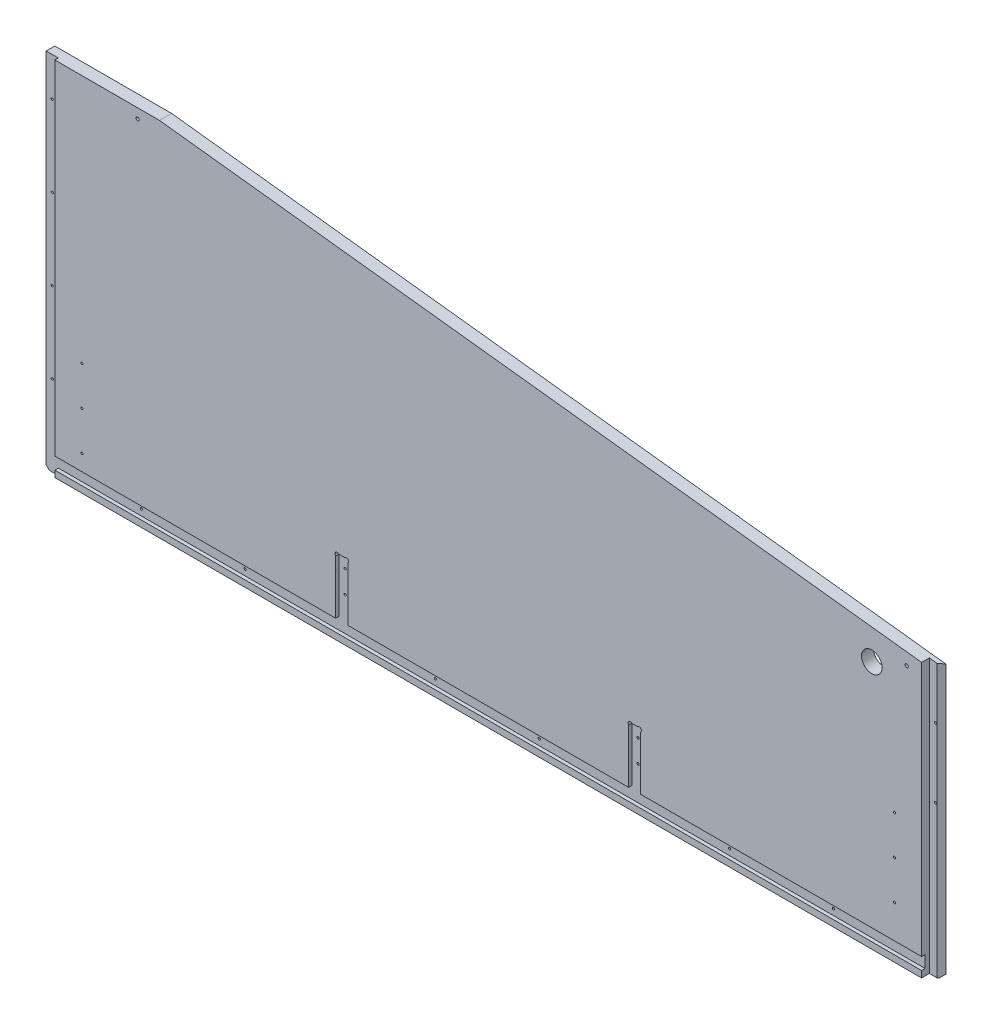
SolidWorks part; units mm, degrees
material "Pine"
ref_plane "Front Plane" through (0, 0, 0) normal (0, 0, 1) x (1, 0, 0)
ref_plane "Top Plane" through (0, 0, 0) normal (0, 1, 0) x (1, 0, 0)
ref_plane "Right Plane" through (0, 0, 0) normal (1, 0, 0) x (0, 0, -1)
sketch "Sketch1" plane through (0, 0, 0) normal (0, 0, 1) x (1, 0, 0)
  line L0 (8932.6508, -5243.5125) -> (10226.1458, -5243.5125)
  line L1 (9086.3208, -4722.0918) -> (10222.9708, -4853.7812)
  line L2 (8914.8708, -6342.0625) -> (10197.5708, -6342.0625)
  line L3 (8914.8708, -5808.6625) -> (10197.5708, -5808.6625)
  line L4 (8919.6333, -5253.0375) -> (10218.2083, -5253.0375)
  line L5 (9134.2633, -4656.1375) -> (9134.2633, -4638.3575)
  line L6 (9091.0833, -4638.3575) -> (9134.2633, -4638.3575)
  line L7 (9091.0833, -4567.2375) -> (9091.0833, -4638.3575)
  line L8 (9134.2633, -4656.1375) -> (9581.3033, -4656.1375)
  line L9 (9091.0833, -4567.2375) -> (9624.4833, -4567.2375)
  line L10 (9581.3033, -4656.1375) -> (9581.3033, -4638.3575)
  line L11 (9581.3033, -4638.3575) -> (9624.4833, -4638.3575)
  line L12 (9624.4833, -4567.2375) -> (9624.4833, -4638.3575)
  line L13 (8932.6508, -5225.7325) -> (9344.9775, -5225.7325)
  line L14 (8932.6508, -5256.2125) -> (8932.6508, -5243.5125)
  line L15 (8911.6958, -5256.2125) -> (8932.6508, -5256.2125)
  line L16 (8914.8708, -4722.0918) -> (9086.3208, -4722.0918)
  line L17 (8911.6958, -4715.5913) -> (8932.6508, -4715.5913)
  line L18 (8914.8708, -6342.0625) -> (8914.8708, -5808.6625)
  line L19 (12082.9917, -4722.0918) -> (10946.3417, -4853.7812)
  line L20 (12236.6617, -5243.5125) -> (10943.1667, -5243.5125)
  line L21 (10951.1042, -5253.0375) -> (12249.6792, -5253.0375)
  line L22 (10838.3917, -5656.2625) -> (11308.2917, -5656.2625)
  line L23 (10838.3917, -5719.7625) -> (11308.2917, -5719.7625)
  line L24 (10838.3917, -5742.5368) -> (11308.2917, -5742.5368)
  line L25 (10806.6417, -6342.0625) -> (11340.0417, -6342.0625)
  line L26 (10803.4667, -6335.7125) -> (11343.2167, -6335.7125)
  line L27 (10803.4667, -6317.9325) -> (11343.2167, -6317.9325)
  line L28 (10943.1667, -5225.7325) -> (11376.4483, -5225.7325)
  line L29 (11506.7292, -4754.5625) -> (10806.6417, -4827.5875)
  line L30 (11506.7292, -4567.2375) -> (11506.7292, -4754.5625)
  line L31 (10806.6417, -4567.2375) -> (10806.6417, -4827.5875)
  line L32 (10806.6417, -4567.2375) -> (11506.7292, -4567.2375)
  line L33 (10235.6708, -6329.3625) -> (10245.1958, -6329.3625)
  line L34 (10245.1958, -6329.3625) -> (10254.7208, -6278.5625)
  line L35 (10302.3458, -6329.3625) -> (10311.8708, -6278.5625)
  line L36 (10302.3458, -6329.3625) -> (10292.8208, -6329.3625)
  line L37 (10245.1958, -5821.3625) -> (10254.7208, -5872.1625)
  line L38 (10235.6708, -5821.3625) -> (10245.1958, -5821.3625)
  line L39 (10292.8208, -5821.3625) -> (10302.3458, -5821.3625)
  line L40 (10302.3458, -5821.3625) -> (10311.8708, -5872.1625)
  line L41 (10235.6708, -5821.3625) -> (10235.6708, -6329.3625)
  line L42 (10254.7208, -5872.1625) -> (10254.7208, -6278.5625)
  line L43 (10311.8708, -5872.1625) -> (10311.8708, -6278.5625)
  line L44 (10292.8208, -5821.3625) -> (10292.8208, -6329.3625)
  line L45 (8932.6508, -5225.7325) -> (8932.6508, -4715.5913)
  line L46 (8911.6958, -4715.5913) -> (8911.6958, -5256.2125)
  line L47 (8914.8708, -5248.275) -> (8914.8708, -4722.0918)
  line L48 (8919.6333, -5253.0375) -> (8914.8708, -5248.275)
  line L49 (8914.8708, -5145.0875) -> (8937.426, -5145.0875)
  line L50 (8914.8708, -5202.2375) -> (8937.426, -5202.2375)
  line L51 (10838.3917, -5656.2625) -> (10838.3917, -5719.7625)
  line L52 (10832.0417, -5736.1868) -> (10856.1717, -5736.1868)
  line L53 (10806.6417, -6342.0625) -> (10806.6417, -5818.7368)
  line L54 (10832.0417, -5649.9125) -> (10856.1717, -5649.9125)
  line L55 (10832.0417, -5726.1125) -> (10856.1717, -5726.1125)
  line L56 (10806.6417, -5818.7368) -> (10833.9015, -5818.7368)
  line L57 (10832.0417, -5806.0442) -> (10851.6815, -5806.0442)
  line L58 (10856.1717, -5801.5541) -> (10856.1717, -5736.1868)
  line L59 (10838.3917, -5814.2467) -> (10838.3917, -5742.5368)
  line L60 (10832.0417, -5806.0442) -> (10832.0417, -5736.1868)
  line L61 (10803.4667, -6317.9325) -> (10803.4667, -6335.7125)
  line L62 (10197.5708, -5808.6625) -> (10197.5708, -6342.0625)
  line L63 (9762.3842, -6348.4125) -> (9762.3842, -5802.3125)
  line L64 (9780.1642, -6348.4125) -> (9762.3842, -6348.4125)
  line L65 (9780.1642, -5802.3125) -> (9780.1642, -6348.4125)
  line L66 (9762.3842, -5802.3125) -> (9780.1642, -5802.3125)
  line L67 (9332.2775, -6348.4125) -> (9332.2775, -5802.3125)
  line L68 (9332.2775, -6348.4125) -> (9350.0575, -6348.4125)
  line L69 (9350.0575, -5802.3125) -> (9350.0575, -6348.4125)
  line L70 (9332.2775, -5802.3125) -> (9350.0575, -5802.3125)
  line L71 (9993.8374, -6061.075) -> (9993.8374, -6045.2418)
  line L72 (9998.5999, -6065.8375) -> (10014.4331, -6065.8375)
  line L73 (9998.5999, -6084.8875) -> (10014.4331, -6084.8875)
  line L74 (9993.8374, -6105.4832) -> (9993.8374, -6089.65)
  line L75 (9974.7874, -6105.4832) -> (9974.7874, -6089.65)
  line L76 (9954.1917, -6084.8875) -> (9970.0249, -6084.8875)
  line L77 (9974.7874, -6061.075) -> (9974.7874, -6045.2418)
  line L78 (9954.1917, -6065.8375) -> (9970.0249, -6065.8375)
  line L79 (10793.9417, -6237.2875) -> (10816.4969, -6237.2875)
  line L80 (10793.9417, -6294.4375) -> (10816.4969, -6294.4375)
  line L81 (10856.1717, -5649.9125) -> (10856.1717, -5726.1125)
  line L82 (10832.0417, -5726.1125) -> (10832.0417, -5649.9125)
  line L83 (10226.1458, -5225.7325) -> (10226.1458, -5243.5125)
  line L84 (10205.1908, -5257.8) -> (10205.1908, -4844.2499)
  line L85 (10230.9083, -4844.2499) -> (10230.9083, -5257.8)
  line L86 (10205.1908, -5257.8) -> (10230.9083, -5257.8)
  line L87 (10205.1908, -4844.2499) -> (10230.9083, -4844.2499)
  line L88 (10946.3417, -5176.8375) -> (10968.8969, -5176.8375)
  line L89 (9349.4676, -5141.9125) -> (9358.2674, -5141.9125)
  line L90 (10946.3417, -5119.6875) -> (10968.8969, -5119.6875)
  line L91 (9929.011, -4660.9635) -> (10066.0807, -4660.9635)
  line L92 (9929.011, -4678.7435) -> (10066.0807, -4678.7435)
  line L93 (10943.1667, -5225.7325) -> (10943.1667, -5243.5125)
  line L94 (10946.3417, -5248.275) -> (10951.1042, -5253.0375)
  line L95 (10946.3417, -5257.8063) -> (10946.3417, -4849.0188)
  line L96 (10964.1217, -5257.8) -> (10964.1217, -4844.2499)
  line L97 (10938.4042, -4844.2499) -> (10938.4042, -5257.8)
  line L98 (10938.4042, -5257.8) -> (10964.1217, -5257.8)
  line L99 (10964.1217, -4844.2499) -> (10938.4042, -4844.2499)
  line L100 (10344.8908, -4560.8875) -> (10369.0208, -4560.8875)
  line L101 (10344.8908, -4560.8875) -> (10369.0208, -4560.8875)
  line L102 (10800.2917, -4560.8875) -> (10824.4217, -4560.8875)
  line L103 (10200.4156, -5119.6875) -> (10222.9708, -5119.6875)
  line L104 (10200.4156, -5176.8375) -> (10222.9708, -5176.8375)
  line L105 (9344.9775, -5146.4026) -> (9344.9775, -5225.7325)
  line L106 (10344.8908, -4560.8875) -> (10344.8908, -4833.9375)
  line L107 (9792.8642, -5225.7325) -> (9792.8642, -5146.4026)
  line L108 (9362.7575, -5225.7325) -> (9775.0842, -5225.7325)
  line L109 (9680.3633, -4761.8396) -> (9680.3633, -4559.9604)
  line L110 (9656.2333, -4559.9604) -> (9680.3633, -4559.9604)
  line L111 (9656.2333, -4761.8396) -> (9680.3633, -4761.8396)
  line L112 (9656.2333, -4761.8396) -> (9656.2333, -4559.9604)
  line L113 (9779.5743, -5141.9125) -> (9788.374, -5141.9125)
  line L114 (10070.5708, -4665.4536) -> (10070.5708, -4674.2534)
  line L115 (9924.5208, -4674.2534) -> (9924.5208, -4665.4536)
  line L116 (12127.4417, -6188.3925) -> (12205.5015, -6188.3925)
  line L117 (12209.9917, -6170.6125) -> (12209.9917, -6183.9024)
  line L118 (9792.8642, -5225.7325) -> (10226.1458, -5225.7325)
  line L119 (9662.5833, -4754.5625) -> (10362.6708, -4827.5875)
  line L120 (9662.5833, -4567.2375) -> (9662.5833, -4754.5625)
  line L121 (10362.6708, -4567.2375) -> (10362.6708, -4827.5875)
  line L122 (9662.5833, -4567.2375) -> (10362.6708, -4567.2375)
  line L123 (10824.4217, -4833.9375) -> (10800.2917, -4833.9375)
  line L124 (10800.2917, -4833.9375) -> (10800.2917, -4560.8875)
  line L125 (10824.4217, -4560.8875) -> (10824.4217, -4833.9375)
  line L126 (10344.8908, -4833.9375) -> (10369.0208, -4833.9375)
  line L127 (10369.0208, -4833.9375) -> (10369.0208, -4560.8875)
  line L128 (10222.9708, -5248.275) -> (10218.2083, -5253.0375)
  line L129 (10222.9708, -5257.8063) -> (10222.9708, -4849.0188)
  line L130 (11734.6544, -5701.375) -> (11739.2301, -5701.375)
  line L131 (9362.7575, -5225.7325) -> (9362.7575, -5146.4026)
  line L132 (9775.0842, -5146.4026) -> (9775.0842, -5225.7325)
  line L133 (11761.3864, -5701.375) -> (11756.8282, -5701.375)
  line L134 (11734.6544, -5693.755) -> (11739.2301, -5693.755)
  line L135 (11761.4039, -5693.755) -> (11756.8282, -5693.755)
  line L136 (11734.6544, -5701.375) -> (11739.2301, -5701.375)
  line L137 (11744.3462, -5721.3024) -> (11744.3462, -5706.4179)
  line L138 (11751.7122, -5721.3024) -> (11751.7122, -5706.4179)
  line L139 (11740.0917, -6170.6125) -> (11740.0917, -6183.9024)
  line L140 (11689.2917, -6188.3925) -> (11822.6417, -6188.3925)
  line L141 (11689.2917, -6348.4093) -> (11689.2917, -6164.2657)
  line L142 (11689.2917, -6164.2657) -> (11746.4417, -6164.2657)
  line L143 (11746.4417, -6164.2657) -> (11746.4417, -6188.3925)
  line L144 (11689.2917, -6164.2657) -> (11746.4417, -6164.2657)
  line L145 (11340.0417, -5818.7368) -> (11340.0417, -6342.0625)
  line L146 (11290.5117, -5726.1125) -> (11314.6417, -5726.1125)
  line L147 (11290.5117, -5649.9125) -> (11290.5117, -5726.1125)
  line L148 (11340.0417, -5818.7368) -> (11312.7818, -5818.7368)
  line L149 (11314.6417, -5806.0442) -> (11295.0018, -5806.0442)
  line L150 (11290.5117, -5801.5541) -> (11290.5117, -5736.1868)
  line L151 (11308.2917, -5814.2467) -> (11308.2917, -5742.5368)
  line L152 (11314.6417, -5806.0442) -> (11314.6417, -5736.1868)
  line L153 (11290.5117, -5736.1868) -> (11314.6417, -5736.1868)
  line L154 (11848.0417, -6267.1325) -> (11962.3417, -6267.1325)
  line L155 (11962.3417, -6267.1325) -> (11962.3417, -6203.6325)
  line L156 (11343.2167, -6317.9325) -> (11343.2167, -6335.7125)
  line L157 (11365.4417, -5656.2625) -> (11365.4417, -5719.7625)
  line L158 (11365.4417, -5656.2625) -> (11479.7417, -5656.2625)
  line L159 (11778.1917, -6071.3937) -> (11802.3217, -6071.3937)
  line L160 (11314.6417, -5726.1125) -> (11314.6417, -5649.9125)
  line L161 (11314.6417, -5649.9125) -> (11290.5117, -5649.9125)
  line L162 (11308.2917, -5719.7625) -> (11308.2917, -5656.2625)
  line L163 (11689.2917, -6348.4093) -> (11713.4217, -6348.4093)
  line L164 (12203.6417, -6164.2657) -> (12260.7917, -6164.2657)
  line L165 (11713.4217, -6348.4093) -> (11713.4217, -6164.2657)
  line L166 (11695.6417, -6342.0625) -> (11695.6417, -6170.6125)
  line L167 (11695.6417, -6048.5337) -> (11699.4517, -6052.3437)
  line L168 (11822.6417, -6292.5325) -> (11822.6417, -6188.3925)
  line L169 (11695.6417, -6342.0625) -> (11695.6417, -6170.6125)
  line L170 (11848.0417, -6203.6325) -> (11962.3417, -6203.6325)
  line L171 (11848.0417, -6203.6325) -> (11848.0417, -6267.1325)
  line L172 (11987.7417, -6267.1325) -> (11987.7417, -6203.6325)
  line L173 (11784.5417, -6077.7437) -> (11784.5417, -6141.2438)
  line L174 (11517.8417, -5656.2625) -> (11632.1417, -5656.2625)
  line L175 (11632.1417, -5656.2625) -> (11632.1417, -5719.7625)
  line L176 (11632.1417, -5719.7625) -> (11517.8417, -5719.7625)
  line L177 (11517.8417, -5719.7625) -> (11517.8417, -5656.2625)
  line L178 (11692.4667, -6028.2137) -> (11692.4667, -6045.9937)
  line L179 (11695.6417, -5979.3188) -> (11718.1969, -5979.3188)
  line L180 (11695.6417, -5922.1687) -> (11718.1969, -5922.1687)
  line L181 (11821.0415, -5722.9375) -> (11821.0415, -5943.6)
  line L182 (11687.7042, -5651.5) -> (11701.9917, -5651.5)
  line L183 (11687.7042, -5651.5) -> (11687.7042, -6055.5251)
  line L184 (11687.7042, -6055.5251) -> (11701.9917, -6055.5251)
  line L185 (11701.9917, -6055.5251) -> (11701.9917, -5651.5)
  line L186 (11695.6417, -6055.2013) -> (11695.6417, -5649.595)
  line L187 (11695.6417, -5656.2625) -> (11695.6417, -6048.5337)
  line L188 (11695.6417, -6170.6125) -> (11740.0917, -6170.6125)
  line L189 (12203.6417, -6164.2657) -> (12203.6417, -6188.3925)
  line L190 (12254.4417, -6342.0625) -> (12254.4417, -6170.6125)
  line L191 (12129.0419, -5943.6) -> (12129.0419, -5722.9375)
  line L192 (12254.4417, -6048.5337) -> (12250.6317, -6052.3437)
  line L193 (12257.6167, -6045.9937) -> (12257.6167, -6028.2137)
  line L194 (12248.0917, -5651.5) -> (12262.3792, -5651.5)
  line L195 (12262.3792, -5651.5) -> (12262.3792, -6055.5251)
  line L196 (12262.3792, -6055.5251) -> (12248.0917, -6055.5251)
  line L197 (12248.0917, -6055.5251) -> (12248.0917, -5651.5)
  line L198 (12254.4417, -6141.2438) -> (12254.4417, -6077.7437)
  line L199 (12236.6617, -6164.2657) -> (12260.7917, -6164.2657)
  line L200 (12102.0417, -6267.1325) -> (11987.7417, -6267.1325)
  line L201 (11330.1865, -6237.2875) -> (11352.7417, -6237.2875)
  line L202 (11330.1865, -6294.4375) -> (11352.7417, -6294.4375)
  line L203 (11474.6617, -5851.8425) -> (11492.4417, -5851.8425)
  line L204 (11474.6617, -5808.6625) -> (11474.6617, -5851.8425)
  line L205 (11403.5417, -5808.6625) -> (11474.6617, -5808.6625)
  line L206 (11492.4417, -5851.8425) -> (11492.4417, -6298.8825)
  line L207 (11403.5417, -6342.0625) -> (11403.5417, -5808.6625)
  line L208 (11474.6617, -6298.8825) -> (11492.4417, -6298.8825)
  line L209 (11474.6617, -6342.0625) -> (11474.6617, -6298.8825)
  line L210 (11403.5417, -6342.0625) -> (11474.6617, -6342.0625)
  line L211 (11619.4417, -5851.8425) -> (11601.6617, -5851.8425)
  line L212 (11601.6617, -5808.6625) -> (11601.6617, -5851.8425)
  line L213 (11530.5417, -5808.6625) -> (11601.6617, -5808.6625)
  line L214 (11619.4417, -5851.8425) -> (11619.4417, -6298.8825)
  line L215 (11530.5417, -6342.0625) -> (11530.5417, -5808.6625)
  line L216 (11619.4417, -6298.8825) -> (11601.6617, -6298.8825)
  line L217 (11601.6617, -6342.0625) -> (11601.6617, -6298.8825)
  line L218 (11530.5417, -6342.0625) -> (11601.6617, -6342.0625)
  line L219 (11479.7417, -5719.7625) -> (11479.7417, -5656.2625)
  line L220 (11365.4417, -5719.7625) -> (11479.7417, -5719.7625)
  line L221 (11778.1917, -6147.5937) -> (11802.3217, -6147.5937)
  line L222 (11802.3217, -6071.3937) -> (11802.3217, -6147.5937)
  line L223 (11778.1917, -6147.5937) -> (11778.1917, -6071.3937)
  line L224 (12254.4417, -5922.1687) -> (12231.8865, -5922.1687)
  line L225 (12254.4417, -5979.3188) -> (12231.8865, -5979.3188)
  line L226 (12254.4417, -6055.2013) -> (12254.4417, -5649.595)
  line L227 (12254.4417, -6048.5337) -> (12254.4417, -5656.2625)
  line L228 (11841.6917, -5702.2873) -> (12108.3917, -5702.2873)
  line L229 (11822.6417, -6292.5325) -> (12127.4417, -6292.5325)
  line L230 (12127.4417, -6292.5325) -> (12127.4417, -6188.3925)
  line L231 (12254.4417, -6170.6125) -> (12209.9917, -6170.6125)
  line L232 (11695.6417, -6342.0625) -> (12254.4417, -6342.0625)
  line L233 (12236.6617, -6348.4093) -> (12260.7917, -6348.4093)
  line L234 (12260.7917, -6348.4093) -> (12260.7917, -6164.2657)
  line L235 (12236.6617, -6348.4093) -> (12236.6617, -6164.2657)
  line L236 (12102.0417, -6203.6325) -> (12102.0417, -6267.1325)
  line L237 (11987.7417, -6203.6325) -> (12102.0417, -6203.6325)
  line L238 (12236.6617, -6147.5937) -> (12236.6617, -6071.3937)
  line L239 (12203.6417, -6188.3925) -> (12260.7917, -6188.3925)
  line L240 (11098.7417, -4665.4536) -> (11098.7417, -4674.2534)
  line L241 (11394.2283, -5146.4026) -> (11394.2283, -5225.7325)
  line L242 (11376.4483, -5225.7325) -> (11376.4483, -5146.4026)
  line L243 (11394.2283, -5225.7325) -> (11806.555, -5225.7325)
  line L244 (11841.6917, -5964.2502) -> (12108.3917, -5964.2502)
  line L245 (12236.6617, -6147.5937) -> (12260.7917, -6147.5937)
  line L246 (12236.6617, -5256.2125) -> (12236.6617, -5243.5125)
  line L247 (12260.7917, -6147.5937) -> (12260.7917, -6071.3937)
  line L248 (12260.7917, -6071.3937) -> (12236.6617, -6071.3937)
  line L249 (12254.4417, -6077.7437) -> (11784.5417, -6077.7437)
  line L250 (11784.5417, -6141.2438) -> (12254.4417, -6141.2438)
  line L252 (12254.4417, -5656.2625) -> (11695.6417, -5656.2625)
  line L253 (11699.4517, -6052.3437) -> (12250.6317, -6052.3437)
  line L254 (11692.4667, -6045.9937) -> (12257.6167, -6045.9937)
  line L255 (11692.4667, -6028.2137) -> (12257.6167, -6028.2137)
  line L256 (11824.335, -5146.4026) -> (11824.335, -5225.7325)
  line L257 (11811.0451, -5141.9125) -> (11819.8449, -5141.9125)
  line L258 (11244.7917, -4674.2534) -> (11244.7917, -4665.4536)
  line L259 (11806.555, -5225.7325) -> (11806.555, -5146.4026)
  line L260 (11488.9492, -4761.8396) -> (11488.9492, -4559.9604)
  line L261 (11488.9492, -4559.9604) -> (11513.0792, -4559.9604)
  line L262 (11488.9492, -4761.8396) -> (11513.0792, -4761.8396)
  line L263 (11513.0792, -4761.8396) -> (11513.0792, -4559.9604)
  line L264 (11240.3015, -4660.9635) -> (11103.2318, -4660.9635)
  line L265 (11103.2318, -4678.7435) -> (11240.3015, -4678.7435)
  line L266 (12236.6617, -5225.7325) -> (12236.6617, -4715.5913)
  line L267 (12257.6167, -4715.5913) -> (12257.6167, -5256.2125)
  line L268 (12254.4417, -5248.275) -> (12254.4417, -4722.0918)
  line L269 (12236.6617, -5225.7325) -> (11824.335, -5225.7325)
  line L270 (12035.0492, -4656.1375) -> (12035.0492, -4638.3575)
  line L271 (12078.2292, -4638.3575) -> (12035.0492, -4638.3575)
  line L272 (12078.2292, -4567.2375) -> (12078.2292, -4638.3575)
  line L273 (12035.0492, -4656.1375) -> (11588.0092, -4656.1375)
  line L274 (11544.8292, -4567.2375) -> (12078.2292, -4567.2375)
  line L275 (11588.0092, -4656.1375) -> (11588.0092, -4638.3575)
  line L276 (11544.8292, -4638.3575) -> (11588.0092, -4638.3575)
  line L277 (11544.8292, -4567.2375) -> (11544.8292, -4638.3575)
  line L278 (12249.6792, -5253.0375) -> (12254.4417, -5248.275)
  line L280 (12257.6167, -5256.2125) -> (12236.6617, -5256.2125)
  line L281 (12231.8865, -5145.0875) -> (12254.4417, -5145.0875)
  line L282 (12231.8865, -5202.2375) -> (12254.4417, -5202.2375)
  line L283 (12236.6617, -4715.5913) -> (12257.6167, -4715.5913)
  line L284 (12082.9917, -4722.0918) -> (12254.4417, -4722.0918)
  line L285 (11380.9385, -5141.9125) -> (11389.7382, -5141.9125)
  circle A0 centre (8923.7608, -4778.9042) radius 1.5875
  circle A1 centre (9062.6598, -4736.3765) radius 2.3685
  circle A2 centre (9051.3958, -6281.7375) radius 22.225
  circle A3 centre (9083.1458, -6249.9875) radius 1.5875
  circle A4 centre (9083.1458, -6313.4875) radius 1.5875
  circle A5 centre (9019.6458, -6249.9875) radius 1.5875
  circle A6 centre (9019.6458, -6313.4875) radius 1.5875
  circle A7 centre (8972.3383, -5202.2375) radius 1.5875
  circle A8 centre (8923.7608, -5015.9708) radius 1.5875
  circle A9 centre (8923.7608, -5134.5042) radius 1.5875
  circle A10 centre (9054.5708, -5234.6225) radius 1.5875
  circle A11 centre (8923.7608, -4897.4375) radius 1.5875
  circle A12 centre (8972.3383, -5087.9375) radius 1.5875
  circle A13 centre (8972.3383, -5145.0875) radius 1.5875
  circle A14 centre (10847.2817, -5668.9625) radius 1.5875
  circle A15 centre (10847.2817, -5707.0625) radius 1.5875
  circle A16 centre (10847.2817, -5755.2368) radius 1.5875
  circle A17 centre (10851.4092, -6237.2875) radius 1.5875
  circle A18 centre (10851.4092, -6294.4375) radius 1.5875
  circle A19 centre (10847.2817, -5793.3442) radius 1.5875
  arc A20 (10833.9015, -5818.7368) -> (10838.3917, -5814.2467) centre (10836.1466, -5816.4918) ccw
  arc A21 (10851.6815, -5806.0442) -> (10856.1717, -5801.5541) centre (10853.9266, -5803.7992) ccw
  circle A22 centre (10882.8417, -6040.4375) radius 1.5875
  circle A23 centre (10882.8417, -6218.2375) radius 1.5875
  circle A24 centre (10882.8417, -5862.6375) radius 1.5875
  circle A25 centre (10908.2417, -6326.8225) radius 1.5875
  circle A26 centre (10908.2417, -6326.8225) radius 1.5875
  circle A27 centre (10851.4092, -6180.1375) radius 1.5875
  circle A28 centre (10815.5317, -4783.4231) radius 1.5875
  circle A29 centre (10815.5317, -4696.9488) radius 1.5875
  circle A30 centre (10815.5317, -4610.4746) radius 1.5875
  circle A31 centre (10979.1323, -4867.0082) radius 2.3685
  circle A32 centre (10190.1802, -4867.0082) radius 2.3685
  circle A33 centre (10955.2317, -4929.9812) radius 1.5875
  circle A34 centre (10955.2317, -5031.5812) radius 1.5875
  circle A35 centre (10214.0808, -4929.9812) radius 1.5875
  circle A36 centre (10214.0808, -5031.5812) radius 1.5875
  circle A37 centre (9341.1675, -6265.8625) radius 1.5875
  circle A38 centre (9771.2742, -5884.8625) radius 1.5875
  circle A39 centre (9771.2742, -6138.8625) radius 1.5875
  circle A40 centre (9771.2742, -6011.8625) radius 1.5875
  arc A41 (10036.2287, -6113.8083) -> (10051.3426, -6111.6033) centre (10042.9639, -6107.0732) ccw
  arc A42 (10051.3426, -6111.6033) -> (10051.3426, -6039.1217) centre (9984.3124, -6075.3625) ccw
  arc A43 (10051.3426, -6039.1217) -> (10036.2287, -6036.9167) centre (10042.9639, -6043.6518) ccw
  arc A44 (10034.5851, -6102.5431) -> (10034.5851, -6048.1819) centre (9984.3124, -6075.3625) ccw
  arc A45 (10034.5851, -6102.5431) -> (10036.2287, -6113.8083) centre (10042.9639, -6107.0732) ccw
  arc A46 (10036.2287, -6036.9167) -> (10034.5851, -6048.1819) centre (10042.9639, -6043.6518) ccw
  arc A47 (9945.8666, -6127.2787) -> (9948.0717, -6142.3927) centre (9952.6018, -6134.0139) ccw
  arc A48 (9948.0717, -6142.3927) -> (10020.5532, -6142.3927) centre (9984.3124, -6075.3625) ccw
  arc A49 (10020.5532, -6142.3927) -> (10022.7583, -6127.2787) centre (10016.0231, -6134.0139) ccw
  arc A50 (9957.1319, -6125.6352) -> (10011.493, -6125.6352) centre (9984.3124, -6075.3625) ccw
  arc A51 (9957.1319, -6125.6352) -> (9945.8666, -6127.2787) centre (9952.6018, -6134.0139) ccw
  arc A52 (10022.7583, -6127.2787) -> (10011.493, -6125.6352) centre (10016.0231, -6134.0139) ccw
  arc A53 (9932.3962, -6036.9167) -> (9917.2822, -6039.1217) centre (9925.661, -6043.6518) ccw
  arc A54 (9917.2822, -6039.1217) -> (9917.2822, -6111.6033) centre (9984.3124, -6075.3625) ccw
  arc A55 (9917.2822, -6111.6033) -> (9932.3962, -6113.8083) centre (9925.661, -6107.0732) ccw
  arc A56 (9934.0398, -6048.1819) -> (9934.0398, -6102.5431) centre (9984.3124, -6075.3625) ccw
  arc A57 (9934.0398, -6048.1819) -> (9932.3962, -6036.9167) centre (9925.661, -6043.6518) ccw
  arc A58 (9932.3962, -6113.8083) -> (9934.0398, -6102.5431) centre (9925.661, -6107.0732) ccw
  arc A59 (9945.8666, -6023.4463) -> (9957.1319, -6025.0898) centre (9952.6018, -6016.7111) ccw
  arc A60 (10011.493, -6025.0898) -> (10022.7583, -6023.4463) centre (10016.0231, -6016.7111) ccw
  arc A61 (10011.493, -6025.0898) -> (9957.1319, -6025.0898) centre (9984.3124, -6075.3625) ccw
  arc A62 (9948.0717, -6008.3323) -> (9945.8666, -6023.4463) centre (9952.6018, -6016.7111) ccw
  arc A63 (10020.5532, -6008.3323) -> (9948.0717, -6008.3323) centre (9984.3124, -6075.3625) ccw
  arc A64 (10022.7583, -6023.4463) -> (10020.5532, -6008.3323) centre (10016.0231, -6016.7111) ccw
  arc A65 (10005.0943, -6187.7574) -> (10096.7073, -6096.1443) centre (9984.3124, -6075.3625) ccw
  arc A66 (9993.8374, -6178.3911) -> (10005.0943, -6187.7574) centre (10003.3624, -6178.3911) ccw
  arc A67 (10001.6306, -6169.0249) -> (10077.9748, -6092.6807) centre (9984.3124, -6075.3625) ccw
  arc A68 (10087.3411, -6084.8875) -> (10077.9748, -6092.6807) centre (10087.3411, -6094.4125) ccw
  arc A69 (10001.6306, -6169.0249) -> (9993.8374, -6178.3911) centre (10003.3624, -6178.3911) ccw
  arc A70 (9963.5306, -6187.7574) -> (9974.7874, -6178.3911) centre (9965.2624, -6178.3911) ccw
  arc A71 (9871.9176, -6096.1443) -> (9963.5306, -6187.7574) centre (9984.3124, -6075.3625) ccw
  arc A72 (9881.2838, -6084.8875) -> (9871.9176, -6096.1443) centre (9881.2838, -6094.4125) ccw
  arc A73 (9890.65, -6092.6807) -> (9966.9943, -6169.0249) centre (9984.3124, -6075.3625) ccw
  arc A74 (9974.7874, -6178.3911) -> (9966.9943, -6169.0249) centre (9965.2624, -6178.3911) ccw
  arc A75 (9890.65, -6092.6807) -> (9881.2838, -6084.8875) centre (9881.2838, -6094.4125) ccw
  arc A76 (9871.9176, -6054.5807) -> (9881.2838, -6065.8375) centre (9881.2838, -6056.3125) ccw
  arc A77 (9963.5306, -5962.9676) -> (9871.9176, -6054.5807) centre (9984.3124, -6075.3625) ccw
  arc A78 (9974.7874, -5972.3339) -> (9963.5306, -5962.9676) centre (9965.2624, -5972.3339) ccw
  arc A79 (9966.9943, -5981.7001) -> (9890.65, -6058.0443) centre (9984.3124, -6075.3625) ccw
  arc A80 (9881.2838, -6065.8375) -> (9890.65, -6058.0443) centre (9881.2838, -6056.3125) ccw
  arc A81 (9966.9943, -5981.7001) -> (9974.7874, -5972.3339) centre (9965.2624, -5972.3339) ccw
  arc A82 (10077.9748, -6058.0443) -> (10087.3411, -6065.8375) centre (10087.3411, -6056.3125) ccw
  arc A83 (9993.8374, -5972.3339) -> (10001.6306, -5981.7001) centre (10003.3624, -5972.3339) ccw
  arc A84 (10077.9748, -6058.0443) -> (10001.6306, -5981.7001) centre (9984.3124, -6075.3625) ccw
  arc A85 (10087.3411, -6065.8375) -> (10096.7073, -6054.5807) centre (10087.3411, -6056.3125) ccw
  arc A86 (10096.7073, -6054.5807) -> (10005.0943, -5962.9676) centre (9984.3124, -6075.3625) ccw
  arc A87 (10005.0943, -5962.9676) -> (9993.8374, -5972.3339) centre (10003.3624, -5972.3339) ccw
  arc A88 (10014.4331, -6065.8375) -> (10018.7361, -6059.0339) centre (10014.4331, -6061.075) ccw
  arc A89 (10018.7361, -6059.0339) -> (10000.641, -6040.9388) centre (9984.3124, -6075.3625) ccw
  arc A90 (10000.641, -6040.9388) -> (9993.8374, -6045.2418) centre (9998.5999, -6045.2418) ccw
  arc A91 (9993.8374, -6061.075) -> (9998.5999, -6065.8375) centre (9998.5999, -6061.075) ccw
  arc A92 (9993.8374, -6105.4832) -> (10000.641, -6109.7862) centre (9998.5999, -6105.4832) ccw
  arc A93 (10000.641, -6109.7862) -> (10018.7361, -6091.6911) centre (9984.3124, -6075.3625) ccw
  arc A94 (10018.7361, -6091.6911) -> (10014.4331, -6084.8875) centre (10014.4331, -6089.65) ccw
  arc A95 (9998.5999, -6084.8875) -> (9993.8374, -6089.65) centre (9998.5999, -6089.65) ccw
  arc A96 (9954.1917, -6084.8875) -> (9949.8888, -6091.6911) centre (9954.1917, -6089.65) ccw
  arc A97 (9949.8888, -6091.6911) -> (9967.9839, -6109.7862) centre (9984.3124, -6075.3625) ccw
  arc A98 (9967.9839, -6109.7862) -> (9974.7874, -6105.4832) centre (9970.0249, -6105.4832) ccw
  arc A99 (9974.7874, -6089.65) -> (9970.0249, -6084.8875) centre (9970.0249, -6089.65) ccw
  arc A100 (9970.0249, -6065.8375) -> (9974.7874, -6061.075) centre (9970.0249, -6061.075) ccw
  arc A101 (9949.8888, -6059.0339) -> (9954.1917, -6065.8375) centre (9954.1917, -6061.075) ccw
  arc A102 (9967.9839, -6040.9388) -> (9949.8888, -6059.0339) centre (9984.3124, -6075.3625) ccw
  arc A103 (9974.7874, -6045.2418) -> (9967.9839, -6040.9388) centre (9970.0249, -6045.2418) ccw
  arc A104 (10096.7073, -6096.1443) -> (10087.3411, -6084.8875) centre (10087.3411, -6094.4125) ccw
  circle A105 centre (9771.2742, -6265.8625) radius 1.5875
  circle A106 centre (9341.1675, -5884.8625) radius 1.5875
  circle A107 centre (9341.1675, -6138.8625) radius 1.5875
  circle A108 centre (9341.1675, -6011.8625) radius 1.5875
  circle A109 centre (11037.2315, -4887.5494) radius 15.0812
  arc A110 (9349.4676, -5141.9125) -> (9344.9775, -5146.4026) centre (9347.2226, -5144.1576) ccw
  arc A111 (9362.7575, -5146.4026) -> (9358.2674, -5141.9125) centre (9360.5124, -5144.1576) ccw
  circle A112 centre (9946.7458, -4669.8535) radius 1.5875
  arc A113 (9924.5208, -4674.2534) -> (9929.011, -4678.7435) centre (9926.7659, -4676.4984) ccw
  circle A114 centre (11003.8092, -5176.8375) radius 1.5875
  circle A115 centre (11003.8092, -5119.6875) radius 1.5875
  circle A116 centre (10353.7808, -4696.9488) radius 1.5875
  circle A117 centre (10353.7808, -4610.4746) radius 1.5875
  circle A118 centre (10353.7808, -4783.4231) radius 1.5875
  circle A119 centre (11003.8092, -5062.5375) radius 1.5875
  circle A120 centre (9353.8675, -5160.9625) radius 1.5875
  circle A121 centre (9638.7708, -5234.6225) radius 1.5875
  circle A122 centre (9671.4733, -4724.1144) radius 1.5875
  circle A123 centre (9671.4733, -4661.3637) radius 1.5875
  circle A124 centre (9671.4733, -4598.6129) radius 1.5875
  arc A125 (9792.8642, -5146.4026) -> (9788.374, -5141.9125) centre (9790.6191, -5144.1576) ccw
  arc A126 (9779.5743, -5141.9125) -> (9775.0842, -5146.4026) centre (9777.3292, -5144.1576) ccw
  circle A127 centre (10048.3458, -4669.8535) radius 1.5875
  arc A128 (10070.5708, -4665.4536) -> (10066.0807, -4660.9635) centre (10068.3258, -4663.2086) ccw
  arc A129 (10066.0807, -4678.7435) -> (10070.5708, -4674.2534) centre (10068.3258, -4676.4984) ccw
  circle A130 centre (9997.5458, -4669.8535) radius 1.5875
  arc A131 (9929.011, -4660.9635) -> (9924.5208, -4665.4536) centre (9926.7659, -4663.2086) ccw
  circle A132 centre (10132.081, -4887.5494) radius 15.0812
  circle A133 centre (10165.5033, -5176.8375) radius 1.5875
  circle A134 centre (10165.5033, -5119.6875) radius 1.5875
  circle A135 centre (9486.3708, -5234.6225) radius 1.5875
  circle A136 centre (10165.5033, -5062.5375) radius 1.5875
  circle A137 centre (9206.9708, -5234.6225) radius 1.5875
  circle A138 centre (10070.5708, -5234.6225) radius 1.5875
  circle A139 centre (9918.1708, -5234.6225) radius 1.5875
  circle A140 centre (9783.9742, -5160.9625) radius 1.5875
  circle A141 centre (9783.9742, -5193.9825) radius 1.5875
  circle A142 centre (9353.8675, -5193.9825) radius 1.5875
  circle A143 centre (11073.3417, -6326.8225) radius 1.5875
  circle A144 centre (11073.3417, -6326.8225) radius 1.5875
  circle A145 centre (11295.2742, -6180.1375) radius 1.5875
  circle A146 centre (11295.2742, -6294.4375) radius 1.5875
  circle A147 centre (11295.2742, -6237.2875) radius 1.5875
  circle A148 centre (11975.0417, -5692.775) radius 3.4925
  circle A149 centre (11263.8417, -5862.6375) radius 1.5875
  arc A150 (11739.2301, -5701.375) -> (11744.3462, -5706.4179) centre (11748.0292, -5697.565) ccw
  arc A151 (11751.7122, -5706.4179) -> (11756.8282, -5701.375) centre (11748.0292, -5697.565) ccw
  arc A152 (11744.3462, -5721.3024) -> (11751.7122, -5721.3024) centre (11748.0292, -5725.505) ccw
  arc A153 (11734.6544, -5693.755) -> (11724.9787, -5697.565) centre (11730.5667, -5697.565) ccw
  arc A154 (11756.8282, -5693.755) -> (11739.2301, -5693.755) centre (11748.0292, -5697.565) ccw
  arc A155 (11724.9787, -5697.565) -> (11734.6544, -5701.375) centre (11730.5667, -5697.565) ccw
  arc A156 (11761.3864, -5701.375) -> (11771.0797, -5697.565) centre (11765.4842, -5697.565) ccw
  arc A157 (11771.0797, -5697.565) -> (11761.4039, -5693.755) centre (11765.4917, -5697.565) ccw
  arc A158 (11740.0917, -6183.9024) -> (11744.5818, -6188.3925) centre (11742.3367, -6186.1474) ccw
  arc A159 (12205.5015, -6188.3925) -> (12209.9917, -6183.9024) centre (12207.7466, -6186.1474) ccw
  circle A160 centre (11299.4017, -5793.3442) radius 1.5875
  arc A161 (11308.2917, -5814.2467) -> (11312.7818, -5818.7368) centre (11310.5367, -5816.4918) ccw
  arc A162 (11290.5117, -5801.5541) -> (11295.0018, -5806.0442) centre (11292.7567, -5803.7992) ccw
  circle A163 centre (11704.5317, -6314.149) radius 1.5875
  circle A164 centre (11748.9817, -6208.7125) radius 1.5875
  circle A165 centre (11263.8417, -6218.2375) radius 1.5875
  circle A166 centre (11263.8417, -6040.4375) radius 1.5875
  circle A167 centre (11238.4417, -6326.8225) radius 1.5875
  circle A168 centre (11238.4417, -6326.8225) radius 1.5875
  circle A169 centre (11299.4017, -5668.9625) radius 1.5875
  circle A170 centre (11299.4017, -5707.0625) radius 1.5875
  circle A171 centre (11726.7567, -6179.5025) radius 1.5875
  circle A172 centre (11704.5317, -6199.3198) radius 1.5875
  circle A173 centre (11748.9817, -6272.2125) radius 1.5875
  circle A174 centre (11704.5317, -6256.7344) radius 1.5875
  circle A175 centre (11299.4017, -5755.2368) radius 1.5875
  circle A176 centre (11913.4467, -6301.4225) radius 1.5875
  circle A177 centre (11790.2567, -6301.4225) radius 1.5875
  circle A178 centre (11793.4317, -6128.5437) radius 1.5875
  circle A179 centre (11753.1092, -5865.0188) radius 1.5875
  circle A180 centre (11809.9417, -6037.1038) radius 1.5875
  circle A181 centre (11809.9417, -6037.1038) radius 1.5875
  circle A182 centre (11753.1092, -5922.1687) radius 1.5875
  circle A183 centre (11975.0417, -5973.7625) radius 3.4925
  circle A184 centre (11975.0417, -6037.1038) radius 1.5875
  circle A185 centre (11753.1092, -5979.3188) radius 1.5875
  circle A186 centre (11975.0417, -6037.1038) radius 1.5875
  arc A187 (11841.6917, -5702.2873) -> (11821.0415, -5722.9375) centre (11841.6917, -5722.9375) ccw
  circle A188 centre (11811.5292, -5833.2687) radius 3.4925
  arc A189 (11821.0415, -5943.6) -> (11841.6917, -5964.2502) centre (11841.6917, -5943.6) ccw
  circle A190 centre (12196.9742, -5865.0188) radius 1.5875
  arc A191 (12129.0419, -5722.9375) -> (12108.3917, -5702.2873) centre (12108.3917, -5722.9375) ccw
  circle A192 centre (12036.6367, -6301.4225) radius 1.5875
  circle A193 centre (12159.8267, -6301.4225) radius 1.5875
  circle A194 centre (12138.5542, -5833.2687) radius 3.4925
  circle A195 centre (12197.2917, -5761.0375) radius 15.0812
  circle A196 centre (11793.4317, -6090.4437) radius 1.5875
  circle A197 centre (12196.9742, -5922.1687) radius 1.5875
  arc A198 (12108.3917, -5964.2502) -> (12129.0419, -5943.6) centre (12108.3917, -5943.6) ccw
  circle A199 centre (12196.9742, -5979.3188) radius 1.5875
  circle A200 centre (12201.1017, -6272.2125) radius 1.5875
  circle A201 centre (12245.5517, -6314.149) radius 1.5875
  circle A202 centre (12245.5517, -6256.7344) radius 1.5875
  circle A203 centre (12201.1017, -6208.7125) radius 1.5875
  circle A204 centre (12223.3267, -6179.5025) radius 1.5875
  circle A205 centre (12245.5517, -6199.3198) radius 1.5875
  circle A206 centre (11171.7667, -4669.8535) radius 1.5875
  circle A207 centre (11222.5667, -4669.8535) radius 1.5875
  arc A208 (11240.3015, -4678.7435) -> (11244.7917, -4674.2534) centre (11242.5466, -4676.4984) ccw
  circle A209 centre (11385.3383, -5193.9825) radius 1.5875
  circle A210 centre (12106.6527, -4736.3765) radius 2.3685
  circle A211 centre (12140.1417, -6037.1038) radius 1.5875
  circle A212 centre (12140.1417, -6037.1038) radius 1.5875
  circle A213 centre (12245.5517, -6090.4437) radius 1.5875
  circle A214 centre (12245.5517, -6128.5437) radius 1.5875
  circle A215 centre (11385.3383, -5160.9625) radius 1.5875
  arc A216 (11824.335, -5146.4026) -> (11819.8449, -5141.9125) centre (11822.0899, -5144.1576) ccw
  arc A217 (11811.0451, -5141.9125) -> (11806.555, -5146.4026) centre (11808.8001, -5144.1576) ccw
  circle A218 centre (11815.445, -5193.9825) radius 1.5875
  circle A219 centre (11815.445, -5160.9625) radius 1.5875
  circle A220 centre (11530.5417, -5234.6225) radius 1.5875
  circle A221 centre (11962.3417, -5234.6225) radius 1.5875
  arc A222 (11244.7917, -4665.4536) -> (11240.3015, -4660.9635) centre (11242.5466, -4663.2086) ccw
  circle A223 centre (11682.9417, -5234.6225) radius 1.5875
  circle A224 centre (11497.8392, -4724.1144) radius 1.5875
  circle A225 centre (11497.8392, -4661.3637) radius 1.5875
  circle A226 centre (11497.8392, -4598.6129) radius 1.5875
  circle A227 centre (11120.9667, -4669.8535) radius 1.5875
  arc A228 (11103.2318, -4660.9635) -> (11098.7417, -4665.4536) centre (11100.9867, -4663.2086) ccw
  arc A229 (11098.7417, -4674.2534) -> (11103.2318, -4678.7435) centre (11100.9867, -4676.4984) ccw
  circle A230 centre (12196.9742, -5202.2375) radius 1.5875
  circle A231 centre (12245.5517, -5015.9708) radius 1.5875
  circle A232 centre (12245.5517, -5134.5042) radius 1.5875
  circle A233 centre (12114.7417, -5234.6225) radius 1.5875
  circle A234 centre (12245.5517, -4897.4375) radius 1.5875
  circle A235 centre (12245.5517, -4778.9042) radius 1.5875
  circle A236 centre (12196.9742, -5087.9375) radius 1.5875
  circle A237 centre (12196.9742, -5145.0875) radius 1.5875
  circle A238 centre (11098.7417, -5234.6225) radius 1.5875
  circle A239 centre (11251.1417, -5234.6225) radius 1.5875
  arc A240 (11380.9385, -5141.9125) -> (11376.4483, -5146.4026) centre (11378.6934, -5144.1576) ccw
  arc A241 (11394.2283, -5146.4026) -> (11389.7382, -5141.9125) centre (11391.9833, -5144.1576) ccw
sketch "Sketch7" plane through (0, 0, 0) normal (0, 0, 1) x (1, 0, 0)
  line L0 (9086.3208, -4722.0918) -> (10222.9708, -4853.7812)
  line L1 (10222.9708, -4853.7812) -> (10222.9708, -5248.275)
  line L2 (10222.9708, -5248.275) -> (10218.2083, -5253.0375)
  line L3 (10218.2083, -5253.0375) -> (8919.6333, -5253.0375)
  line L4 (8919.6333, -5253.0375) -> (8914.8708, -5248.275)
  line L5 (8914.8708, -5248.275) -> (8914.8708, -4722.0918)
  line L6 (8914.8708, -4722.0918) -> (9086.3208, -4722.0918)
extrude "Extrude2" add sketch "Sketch7" against normal blind 17.78
sketch "Sketch8" plane through (0, 0, 0) normal (0, 0, 1) x (1, 0, 0)
  line L0 (8932.6508, -4722.0918) -> (8914.8708, -4722.0918)
  line L1 (8914.8708, -4722.0918) -> (8914.8708, -5253.0375)
  line L2 (8914.8708, -5253.0375) -> (8932.6508, -5253.0375)
  line L3 (8932.6508, -5253.0375) -> (8932.6508, -5243.5125)
  line L4 (8932.6508, -5243.5125) -> (10222.9708, -5243.5125)
  line L5 (10222.9708, -5243.5125) -> (10222.9708, -5225.7325)
  line L6 (10222.9708, -5225.7325) -> (9792.8642, -5225.7325)
  line L7 (9792.8642, -5225.7325) -> (9792.8642, -5141.9125)
  line L8 (10222.9708, -5248.275) -> (10222.9708, -4853.7812) construction
  line L9 (9792.8642, -5141.9125) -> (9775.0842, -5141.9125)
  line L11 (9775.0842, -5141.9125) -> (9775.0842, -5225.7325)
  line L12 (9775.0842, -5225.7325) -> (9362.7575, -5225.7325)
  line L13 (9362.7575, -5225.7325) -> (9362.7575, -5141.9125)
  line L15 (9362.7575, -5141.9125) -> (9344.9775, -5141.9125)
  line L17 (9344.9775, -5141.9125) -> (9344.9775, -5225.7325)
  line L18 (9344.9775, -5225.7325) -> (8932.6508, -5225.7325)
  line L19 (8932.6508, -5225.7325) -> (8932.6508, -4722.0918)
  line L20 (9086.3208, -4722.0918) -> (8914.8708, -4722.0918) construction
  line L21 (8919.6333, -5253.0375) -> (10218.2083, -5253.0375) construction
  dimension "D1" = 17.78
  dimension "D2" = 17.78
  dimension "D3" = 17.78
  dimension "D4" = 17.78
  dimension "D5" = 17.78
extrude "Cut-Extrude3" cut sketch "Sketch8" against normal blind 5.08
sketch "Sketch9" plane through (0, 0, 0) normal (0, 0, 1) x (1, 0, 0)
  line L0 (9344.9775, -5141.9125) -> (9347.2226, -5144.1576) construction
  line L1 (9344.9775, -5141.9125) -> (9344.9775, -5225.7325) construction
  line L2 (9362.7575, -5141.9125) -> (9360.5124, -5144.1576) construction
  line L3 (9362.7575, -5225.7325) -> (9362.7575, -5141.9125) construction
  line L4 (9775.0842, -5141.9125) -> (9777.3292, -5144.1576) construction
  line L5 (9792.8642, -5141.9125) -> (9790.6191, -5144.1576) construction
  line L6 (9775.0842, -5141.9125) -> (9775.0842, -5225.7325) construction
  line L8 (9792.8642, -5225.7325) -> (9792.8642, -5141.9125) construction
  circle A0 centre (9347.2226, -5144.1576) radius 3.302
  circle A1 centre (9360.5124, -5144.1576) radius 3.175
  circle A2 centre (9777.3292, -5144.1576) radius 3.175
  circle A3 centre (9790.6191, -5144.1576) radius 3.175
  dimension "D1" = 45
  dimension "D2" = 3.175
  dimension "D3" = 45
  dimension "D4" = 3.175
  dimension "D5" = 45
  dimension "D6" = 3.175
  dimension "D7" = 3.175
  dimension "D8" = 45
extrude "Cut-Extrude4" cut sketch "Sketch9" against normal blind 5.08
sketch "Sketch10" plane through (0, 0, 0) normal (0, 0, 1) x (1, 0, 0)
  circle A0 centre (10132.081, -4887.5494) radius 15.0813
  circle A2 centre (8923.7608, -4778.9042) radius 1.5875
  circle A3 centre (8923.7608, -4897.4375) radius 1.5875
  circle A4 centre (8923.7608, -5015.9708) radius 1.5875
  circle A5 centre (8923.7608, -5134.5042) radius 1.5875
  circle A6 centre (9054.5708, -5234.6225) radius 1.5875
  circle A7 centre (9206.9708, -5234.6225) radius 1.5875
  circle A8 centre (9353.8675, -5193.9825) radius 1.5875
  circle A9 centre (9353.8675, -5160.9625) radius 1.5875
  circle A10 centre (9486.3708, -5234.6225) radius 1.5875
  circle A11 centre (9638.7708, -5234.6225) radius 1.5875
  circle A12 centre (9783.9742, -5193.9825) radius 1.5875
  circle A13 centre (9783.9742, -5160.9625) radius 1.5875
  circle A14 centre (9918.1708, -5234.6225) radius 1.5875
  circle A15 centre (10070.5708, -5234.6225) radius 1.5875
  circle A16 centre (10214.0808, -5031.5812) radius 1.5875
  circle A17 centre (10214.0808, -4929.9812) radius 1.5875
  circle A19 centre (8972.3383, -5087.9375) radius 1.5875
  circle A20 centre (8972.3383, -5145.0875) radius 1.5875
  circle A21 centre (8972.3383, -5202.2375) radius 1.5875
  circle A22 centre (10165.5033, -5176.8375) radius 1.5875
  circle A23 centre (10165.5033, -5119.6875) radius 1.5875
  circle A24 centre (10165.5033, -5062.5375) radius 1.5875
extrude "Cut-Extrude5" cut sketch "Sketch10" against normal up to surface (17.78 mm away) up to face at (9499.978, -5042.9414, -17.78)
sketch "Sketch11" plane through (0, 0, 0) normal (0, 0, 1) x (1, 0, 0)
  line L0 (10205.1908, -5253.0375) -> (10222.9708, -5253.0375)
  line L1 (10222.9708, -5253.0375) -> (10222.9708, -4851.7213)
  line L2 (10222.9708, -4851.7213) -> (10205.1908, -4851.7213)
  line L3 (10205.1908, -4851.7213) -> (10205.1908, -5253.0375)
  line L4 (8932.6508, -5253.0375) -> (10218.2083, -5253.0375) construction
  line L5 (10222.9708, -4853.7812) -> (9086.3208, -4722.0918) construction
  dimension "D1" = 17.78
extrude "Cut-Extrude6" cut sketch "Sketch11" against normal blind 11.43
sketch "Sketch14" plane through (0, -5253.0375, 0) normal (0, -1, 0) x (1, 0, 0)
  line L0 (10205.1908, 0) -> (10222.9708, 0) construction
  line L1 (10222.9708, -17.78) -> (10222.9708, 0) construction
  line L2 (10222.9708, -11.43) -> (10229.3208, -11.43)
  line L3 (10222.9708, -11.43) -> (10216.6208, -11.43)
  line L5 (10229.3208, -11.43) -> (10222.9708, -17.78)
  line L6 (10222.9708, -17.78) -> (10216.6208, -11.43)
  dimension "D1" = 17.78
  dimension "D2" = 17.78
  dimension "D3" = 45
  dimension "D4" = 6.35
extrude "Cut-Extrude8" cut sketch "Sketch14" against normal up to surface (530.9457 mm away) up to face at (8977.9475, -4722.0918, -7.62)
sketch "Sketch15" plane through (0, 0, -17.78) normal (0, 0, -1) x (-1, 0, 0)
  line L0 (-10185.6999, -4867.215) -> (-10180.969, -4866.6669) construction
  line L1 (-10185.4258, -4869.5805) -> (-10185.9739, -4864.8496) construction
  line L2 (-10181.2431, -4864.3015) -> (-10180.695, -4869.0324) construction
  line L3 (-9056.6025, -4736.4007) -> (-9051.8717, -4735.8526) construction
  line L4 (-9056.3285, -4738.7661) -> (-9056.8766, -4734.0352) construction
  line L5 (-9052.1457, -4733.4871) -> (-9051.5976, -4738.218) construction
  circle A0 centre (-10183.3344, -4866.941) radius 2.3812
  circle A1 centre (-9054.2371, -4736.1266) radius 2.3812
extrude "Cut-Extrude9" cut sketch "Sketch15" against normal up to surface (17.78 mm away) up to face at (10167.0908, -5062.5375, 0)
